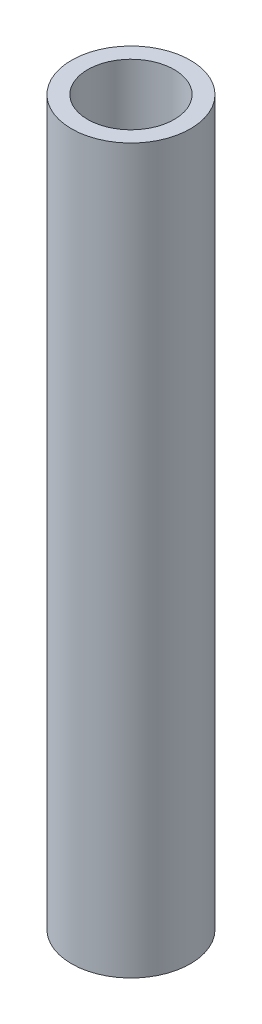
SolidWorks part; units mm, degrees
ref_plane "Front Plane" through (0, 0, 0) normal (0, 0, 1) x (1, 0, 0)
ref_plane "Top Plane" through (0, 0, 0) normal (0, 1, 0) x (1, 0, 0)
ref_plane "Right Plane" through (0, 0, 0) normal (1, 0, 0) x (0, 0, -1)
sketch "Sketch1" plane through (0, 0, 0) normal (0, 1, 0) x (1, 0, 0)
  circle A0 centre (0, 0) radius 12.1539
  circle A1 centre (0, 0) radius 16.7005
  dimension "D1" = 24.3078
  dimension "D2" = 33.401
extrude "Boss-Extrude1" add sketch "Sketch1" along normal mid plane 203.2
